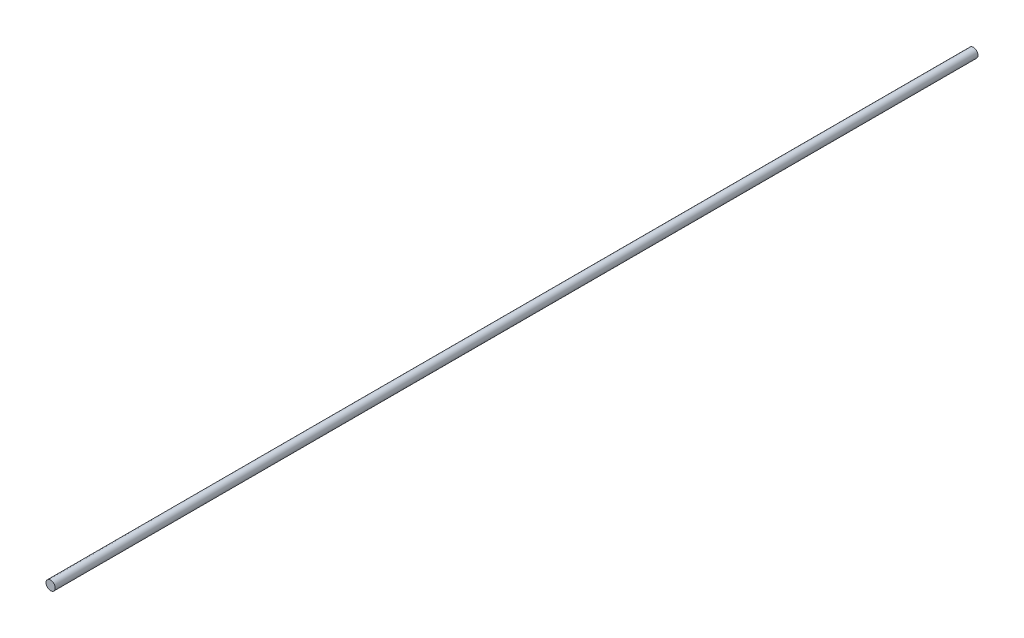
SolidWorks part; units mm, degrees
material "1.4000 (X6Cr13)"
ref_plane "Plan de face" through (0, 0, 0) normal (0, 0, 1) x (1, 0, 0)
ref_plane "Plan de dessus" through (0, 0, 0) normal (0, 1, 0) x (1, 0, 0)
ref_plane "Plan de droite" through (0, 0, 0) normal (1, 0, 0) x (0, 0, -1)
sketch "Esquisse1" plane through (0, 0, 0) normal (0, 0, 1) x (1, 0, 0)
  circle A0 centre (0, 0) radius 2.5
extrude "Boss.-Extru.1" add sketch "Esquisse1" along normal blind 500
